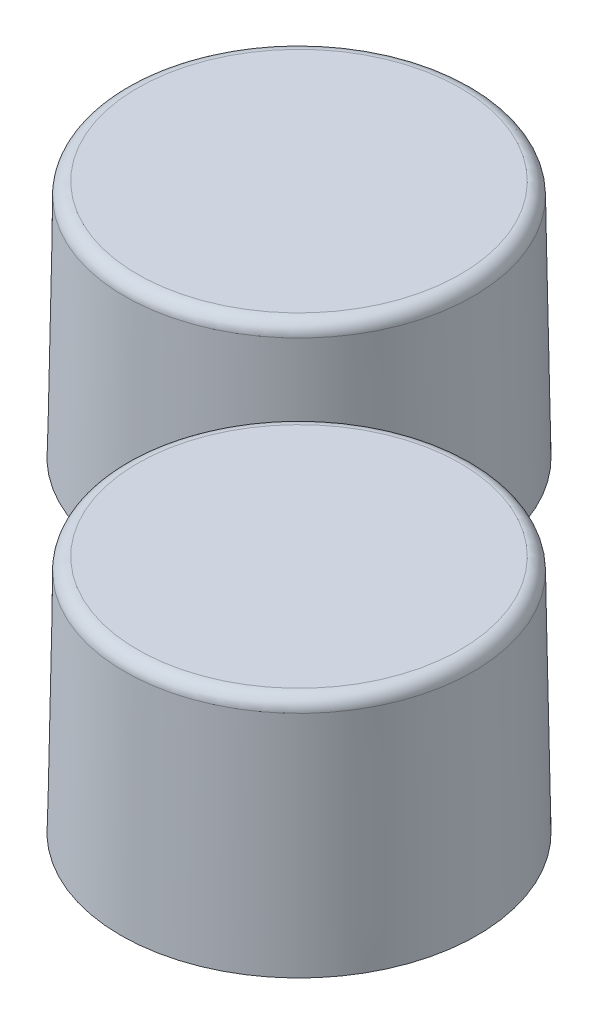
SolidWorks part; units mm, degrees
ref_plane "Front Plane" through (0, 0, 0) normal (0, 0, 1) x (1, 0, 0)
ref_plane "Top Plane" through (0, 0, 0) normal (0, 1, 0) x (1, 0, 0)
ref_plane "Right Plane" through (0, 0, 0) normal (1, 0, 0) x (0, 0, -1)
ref_plane "Plane1" through (173.4443, 0, -173.4443) normal (0.7071, 0, -0.7071) x (-0.7071, 0, -0.7071)
sketch "Sketch3" plane through (173.4443, 0, -173.4443) normal (0.7071, 0, -0.7071) x (-0.7071, 0, -0.7071)
  line L0 (-61.3675, 128.1205) -> (-60.6687, 168.1526)
  line L1 (-60.1688, 168.6439) -> (-31.6202, 168.6439)
  line L2 (-31.6202, 168.6439) -> (-31.6202, 170.4219)
  line L3 (-63.1452, 128.1515) -> (-62.4464, 168.1836)
  line L4 (-60.1688, 170.4219) -> (-31.6202, 170.4219)
  line L5 (-60.1688, 170.4219) -> (-3.0715, 170.4219) construction
  line L7 (-60.1688, 168.6439) -> (-3.0715, 168.6439) construction
  line L8 (-63.1452, 128.1515) -> (-61.3675, 128.1205)
  line L9 (-63.389, 114.1836) -> (-62.4464, 168.1836) construction
  line L10 (-61.6113, 114.1526) -> (-60.6687, 168.1526) construction
  line L11 (-31.6202, 170.4219) -> (-31.6202, 181.7875) construction
  arc A0 (-60.6687, 168.1526) -> (-60.1688, 168.6439) centre (-60.1688, 168.1439) cw
  arc A1 (-62.4464, 168.1836) -> (-60.1688, 170.4219) centre (-60.1688, 168.1439) cw
  dimension "D1" = 1.778
revolve "Revolve1" add sketch "Sketch3" angle 360 about L11
sketch "Sketch4" plane through (173.4443, 0, -173.4443) normal (0.7071, 0, -0.7071) x (-0.7071, 0, -0.7071)
  line L0 (19.9243, 128.064) -> (20.6233, 168.1526)
  line L1 (21.1232, 168.6439) -> (49.6718, 168.6439)
  line L2 (49.6718, 168.6439) -> (49.6718, 170.6984) construction
  line L3 (18.1465, 128.095) -> (18.8455, 168.1836)
  line L4 (21.1232, 170.4219) -> (49.6718, 170.4219)
  line L5 (17.903, 114.1271) -> (18.8455, 168.1836) construction
  line L6 (19.9243, 128.064) -> (18.1465, 128.095)
  line L7 (19.6807, 114.0961) -> (20.6233, 168.1526) construction
  line L8 (49.6718, 168.6439) -> (49.6718, 170.4219)
  arc A0 (21.1232, 168.6439) -> (20.6233, 168.1526) centre (21.1232, 168.1439) ccw
  arc A1 (21.1232, 170.4219) -> (18.8455, 168.1836) centre (21.1232, 168.1439) ccw
  dimension "D1" = 1.778
revolve "Revolve2" add sketch "Sketch4" angle 360 about L8
